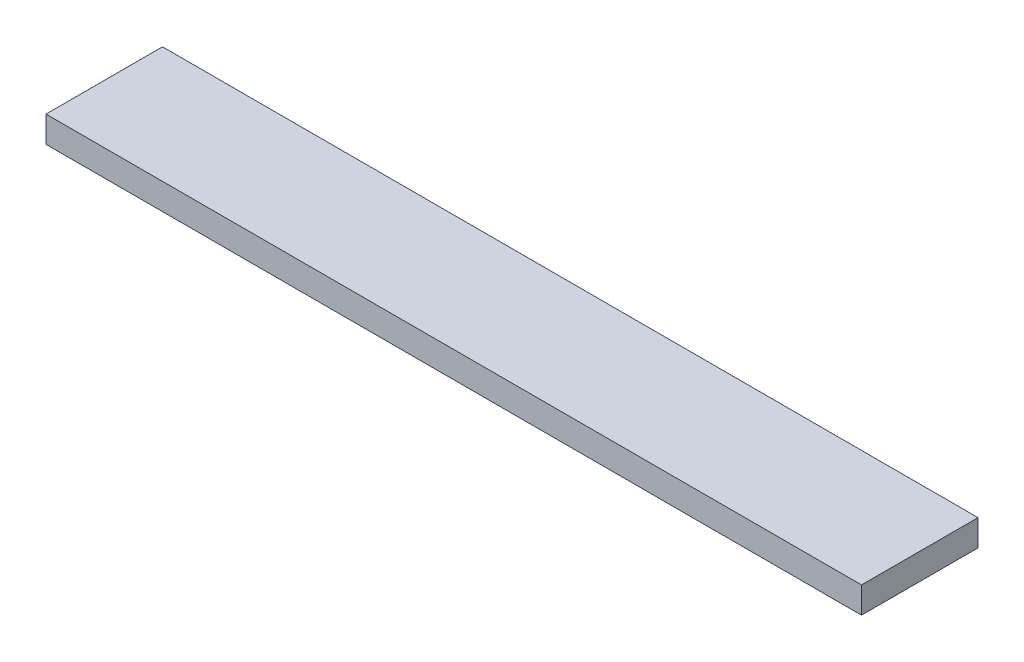
SolidWorks part; units mm, degrees
ref_plane "Front Plane" through (0, 0, 0) normal (0, 0, 1) x (1, 0, 0)
ref_plane "Top Plane" through (0, 0, 0) normal (0, 1, 0) x (1, 0, 0)
ref_plane "Right Plane" through (0, 0, 0) normal (1, 0, 0) x (0, 0, -1)
sketch "Sketch1" plane through (0, 0, 0) normal (0, 1, 0) x (1, 0, 0)
  line L1 (0, 0) -> (140, 0)
  line L2 (0, 0) -> (0, 20)
  line L3 (0, 20) -> (140, 20)
  line L4 (140, 0) -> (140, 20)
  dimension "D1" = 20
  dimension "D2" = 140
extrude "Boss-Extrude1" add sketch "Sketch1" along normal blind 4.5
